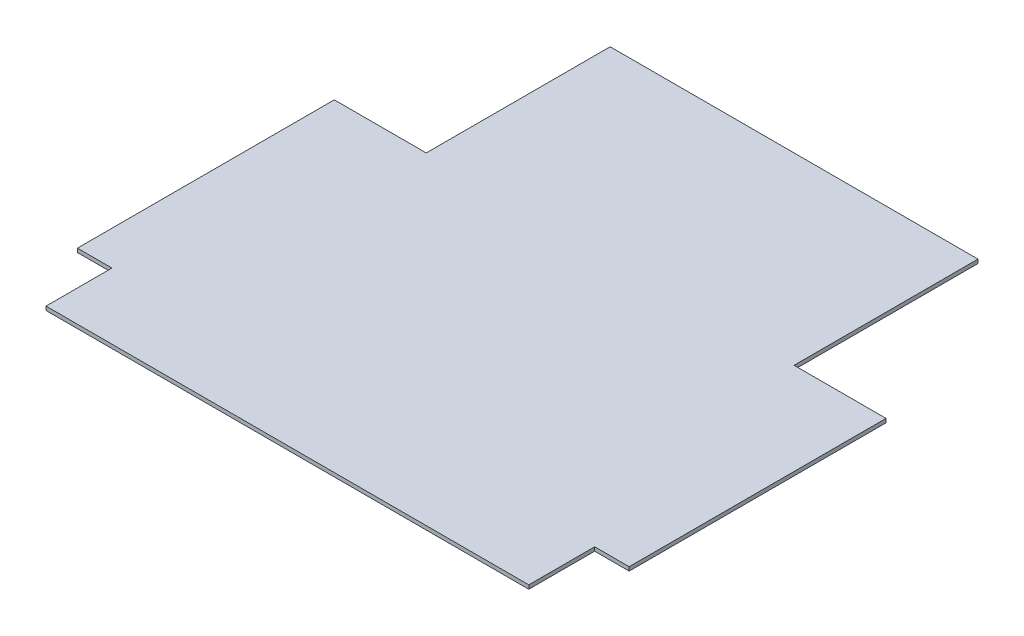
SolidWorks part; units mm, degrees
material "Acrylic (Medium-high impact)"
ref_plane "Front Plane" through (0, 0, 0) normal (0, 0, 1) x (1, 0, 0)
ref_plane "Top Plane" through (0, 0, 0) normal (0, 1, 0) x (1, 0, 0)
ref_plane "Right Plane" through (0, 0, 0) normal (1, 0, 0) x (0, 0, -1)
sketch "Sketch1" plane through (0, 0, 0) normal (0, 1, 0) x (1, 0, 0)
  line L0 (381, 212.852) -> (457.2, 212.852)
  line L1 (0, 0) -> (28.575, 0)
  line L2 (0, 0) -> (0, 212.852)
  line L3 (0, 212.852) -> (76.2, 212.852)
  line L4 (457.2, 0) -> (457.2, 212.852)
  line L5 (76.2, 365.252) -> (381, 365.252)
  line L6 (76.2, 212.852) -> (76.2, 365.252)
  line L7 (428.625, 0) -> (457.2, 0)
  line L8 (381, 212.852) -> (381, 365.252)
  line L14 (28.575, 0) -> (28.575, -54.61)
  line L15 (28.575, -54.61) -> (428.625, -54.61)
  line L16 (428.625, 0) -> (428.625, -54.61)
  dimension "D1" = 457.2
  dimension "D2" = 212.852
  dimension "D3" = 28.575
  dimension "D4" = 76.2
  dimension "D5" = 76.2
  dimension "D6" = 304.8
  dimension "D7" = 457.2
  dimension "D8" = 400.05
  dimension "D10" = 28.575
  dimension "D11" = 54.61
extrude "Boss-Extrude1" add sketch "Sketch1" along normal blind 3.175
